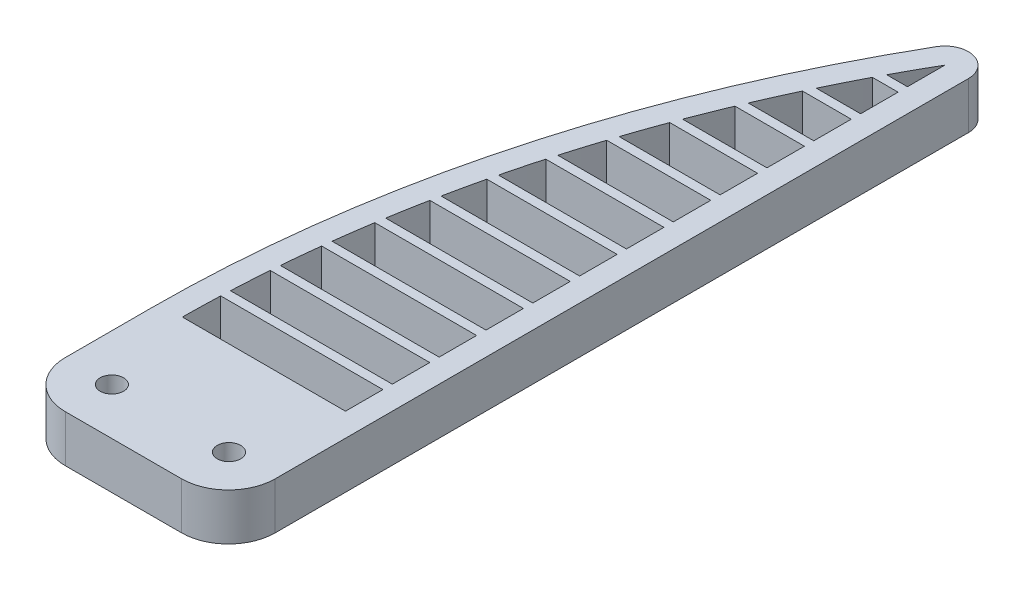
SolidWorks part; units mm, degrees
material "Rubber"
ref_plane "Front Plane" through (0, 0, 0) normal (0, 0, 1) x (1, 0, 0)
ref_plane "Top Plane" through (0, 0, 0) normal (0, 1, 0) x (1, 0, 0)
ref_plane "Right Plane" through (0, 0, 0) normal (1, 0, 0) x (0, 0, -1)
sketch "Sketch1" plane through (0, 0, 0) normal (0, 1, 0) x (1, 0, 0)
  line L0 (0, 0) -> (0, 130)
  line L1 (0, 0) -> (225.1666, 0)
  line L2 (0, 130) -> (225.1666, 0) construction
  line L3 (0, 0) -> (-34.8334, 0)
  line L4 (0, 2) -> (-34.8257, 2)
  line L5 (0, 10) -> (-34.641, 10)
  line L6 (0, 12) -> (-34.5563, 12)
  line L7 (0, 20) -> (-34.063, 20)
  line L8 (0, 22) -> (-33.901, 22)
  line L9 (0, 30) -> (-33.0968, 30)
  line L10 (0, 32) -> (-32.8566, 32)
  line L11 (0, 40) -> (-31.738, 40)
  line L12 (0, 42) -> (-31.4187, 42)
  line L13 (0, 50) -> (-29.9804, 50)
  line L14 (0, 52) -> (-29.5803, 52)
  line L15 (0, 60) -> (-27.8156, 60)
  line L16 (0, 62) -> (-27.3329, 62)
  line L17 (0, 70) -> (-25.2331, 70)
  line L18 (0, 72) -> (-24.6653, 72)
  line L19 (0, 80) -> (-22.2197, 80)
  line L20 (0, 82) -> (-21.564, 82)
  line L21 (0, 90) -> (-18.7596, 90)
  line L22 (0, 92) -> (-18.0123, 92)
  line L23 (0, 100) -> (-14.8334, 100)
  line L24 (0, 102) -> (-13.9902, 102)
  line L25 (0, 110) -> (-10.4178, 110)
  line L26 (0, 112) -> (-9.4735, 112)
  line L27 (0, 120) -> (-5.4846, 120)
  line L28 (0, 122) -> (-4.433, 122)
  line L29 (5, 0) -> (5, 130)
  line L30 (5, 130) -> (0, 130)
  line L31 (225.1666, 0) -> (-1.7138, 136.9317) construction
  line L32 (-34.8334, 0) -> (-39.8334, 0)
  line L33 (0, 130) -> (2.609, 134.3227)
  line L34 (0, 130) -> (-1.7138, 136.9317)
  line L35 (5, 130) -> (5, 132.8796)
  line L36 (-34.8334, 0) -> (-34.8334, -8)
  line L37 (-34.8334, -8) -> (0, -8)
  line L38 (0, -8) -> (0, 0)
  line L39 (-34.8334, -8) -> (0, -8)
  line L40 (-34.8334, -8) -> (-34.8334, -28)
  line L41 (0, -8) -> (0, -28)
  line L42 (-34.8334, -28) -> (0, -28)
  line L43 (-39.8334, -18) -> (0, -18)
  line L44 (-39.8334, 0) -> (-39.8334, -28)
  line L45 (-39.8334, -28) -> (-34.8334, -28)
  line L46 (-19.9167, -18) -> (-39.8334, -18)
  line L47 (-19.9167, -18) -> (0, -18)
  line L48 (-19.9167, -18) -> (0, -18)
  line L49 (-29.875, -15.5) -> (-4.875, -15.5)
  line L50 (5, 0) -> (5, -28)
  line L51 (5, -28) -> (0, -28)
  arc A0 (0, 130) -> (-34.8334, 0) centre (225.1666, 0) ccw
  arc A1 (-1.7138, 136.9317) -> (-39.8334, 0) centre (225.1666, 0) ccw
  arc A2 (5, 130) -> (-4.3301, 132.5) centre (0, 130) ccw
  circle A3 centre (-29.875, -18) radius 2.5
  circle A4 centre (-4.875, -18) radius 2.5
  point P52 (-7.4167, 100)
  point P68 (-29.875, -18)
  point P69 (-4.875, -18)
  point P74 (-19.9167, -18)
  dimension "D28" = 5
  dimension "D33" = 5
  dimension "D35" = 5
  dimension "D1" = 30
  dimension "D2" = 130
  dimension "D3" = 2
  dimension "D4" = 2
  dimension "D5" = 2
  dimension "D6" = 2
  dimension "D7" = 2
  dimension "D8" = 2
  dimension "D9" = 2
  dimension "D10" = 2
  dimension "D11" = 2
  dimension "D12" = 2
  dimension "D13" = 2
  dimension "D14" = 8
  dimension "D15" = 8
  dimension "D16" = 2
  dimension "D17" = 8
  dimension "D18" = 8
  dimension "D19" = 8
  dimension "D20" = 8
  dimension "D21" = 8
  dimension "D22" = 8
  dimension "D23" = 8
  dimension "D24" = 8
  dimension "D25" = 8
  dimension "D26" = 2
  dimension "D27" = 8
  dimension "D29" = 5
  dimension "D30" = 45
  dimension "D31" = 8
  dimension "D32" = 10
  dimension "D34" = 25
extrude "Boss-Extrude1" add sketch "Sketch1" along normal blind 10 contours L4 A0 L3 L0 | L29 L30 L0 L1 | L6 A0 L5 L0 | L34 A2 A1 L32 A0 | L8 A0 L7 L0 | L10 A0 L9 L0 | L12 A0 L11 L0 | L14 A0 L13 L0 | L33 A2 L34 | L30 A2 L33 | L28 A0 L27 L0 | L26 A0 L25 L0 | L24 A0 L23 L0 | L22 A0 L21 L0 | L20 A0 L19 L0 | L18 A0 L17 L0 | L16 A0 L15 L0 | L37 L38 L3 L36 | L32 L44 L43 L40 L36 | L44 L45 L40 L43 | A4 L43 A3 L40 L42 L41 | A4 L43 L41 L37 L40 A3 L49 | A4 L49 A3 L43 | L51 L50 L1 L38 L41
fillet "Fillet1" radius 10 2 edges at (5, 5, 28) (-39.8334, 5, 28)
equation "\"m\"= \"SW-Mass\""
